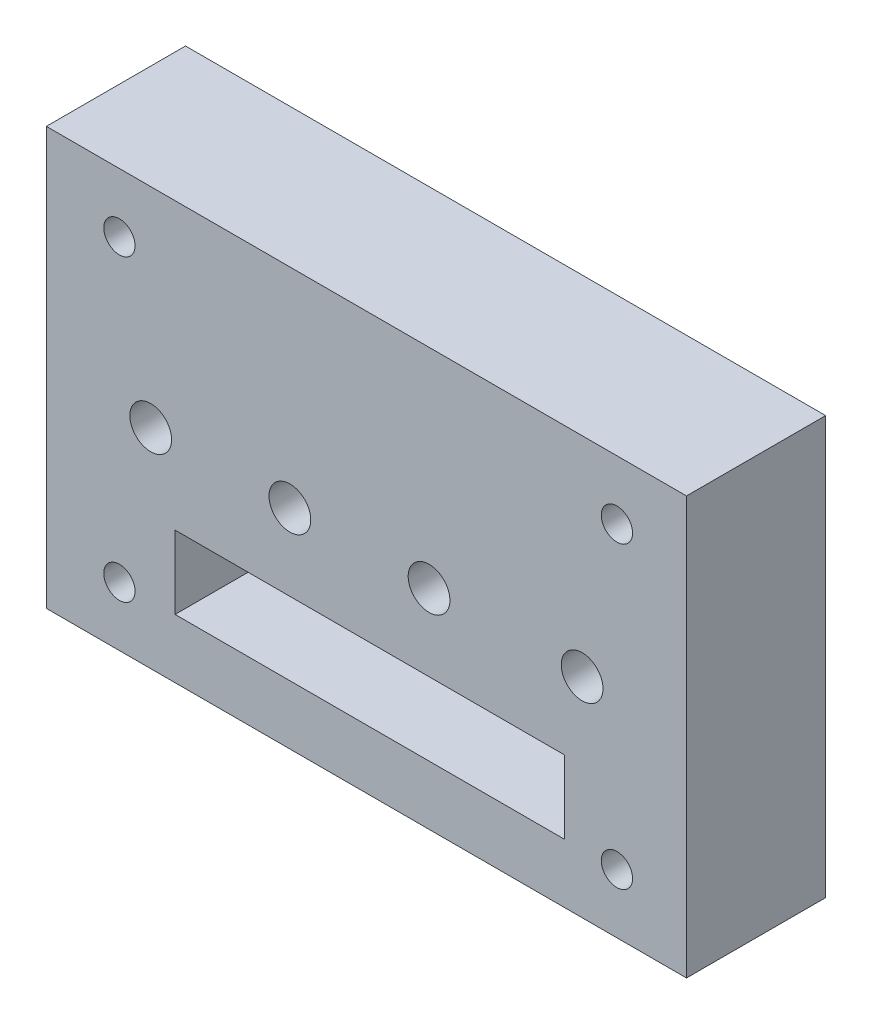
SolidWorks part; units mm, degrees
ref_plane "Front Plane" through (0, 0, 0) normal (0, 0, 1) x (1, 0, 0)
ref_plane "Top Plane" through (0, 0, 0) normal (0, 1, 0) x (1, 0, 0)
ref_plane "Right Plane" through (0, 0, 0) normal (1, 0, 0) x (0, 0, -1)
sketch "Sketch3" plane through (0, 0, 0) normal (0, 0, 1) x (1, 0, 0)
  line L1 (0, 0) -> (92, 0)
  line L2 (0, 0) -> (0, 60)
  line L3 (0, 60) -> (92, 60)
  line L4 (92, 0) -> (92, 60)
  line L5 (8, 54) -> (84.5, 54)
  line L6 (8, 54) -> (8, 6)
  line L7 (8, 6) -> (84.5, 6)
  line L8 (84.5, 54) -> (84.5, 6)
  line L25 (18.5, 19) -> (74.5, 19)
  line L26 (18.5, 19) -> (18.5, 8.5)
  line L27 (18.5, 8.5) -> (74.5, 8.5)
  line L28 (74.5, 19) -> (74.5, 8.5)
  circle A0 centre (15, 30) radius 3
  circle A1 centre (35, 30) radius 3
  circle A2 centre (55, 30) radius 3
  circle A3 centre (77, 30) radius 3
  circle A4 centre (82, 51.5) radius 2.25
  circle A5 centre (82, 8.5) radius 2.25
  circle A6 centre (10.5, 8.5) radius 2.25
  circle A7 centre (10.5, 51.5) radius 2.25
  point P21 (18.5, 13.75)
  point P30 (0, 0)
  dimension "D11" = 6
  dimension "D12" = 6
  dimension "D13" = 6
  dimension "D14" = 6
  dimension "D23" = 4.5
  dimension "D24" = 4.5
  dimension "D25" = 4.5
  dimension "D26" = 4.5
  dimension "D1" = 60
  dimension "D2" = 92
  dimension "D3" = 48
  dimension "D4" = 76.5
  dimension "D5" = 6
  dimension "D6" = 8
  dimension "D7" = 7
  dimension "D8" = 20
  dimension "D9" = 20
  dimension "D10" = 22
  dimension "D15" = 24
  dimension "D16" = 24
  dimension "D17" = 24
  dimension "D18" = 24
  dimension "D19" = 10.5
  dimension "D20" = 56
  dimension "D21" = 10.5
  dimension "D22" = 2.5
  dimension "D27" = 2.5
  dimension "D28" = 2.5
  dimension "D29" = 2.5
  dimension "D30" = 2.5
  dimension "D31" = 2.5
  dimension "D32" = 2.5
  dimension "D33" = 2.5
  dimension "D34" = 2.5
extrude "Boss-Extrude3" add sketch "Sketch3" along normal blind 20 contours L8 L5 L6 L7 A7 A6 A5 A4 A3 A2 A1 A0 L25 L28 L27 L26 | L1 L4 L3 L2 L5 L8 L7 L6
